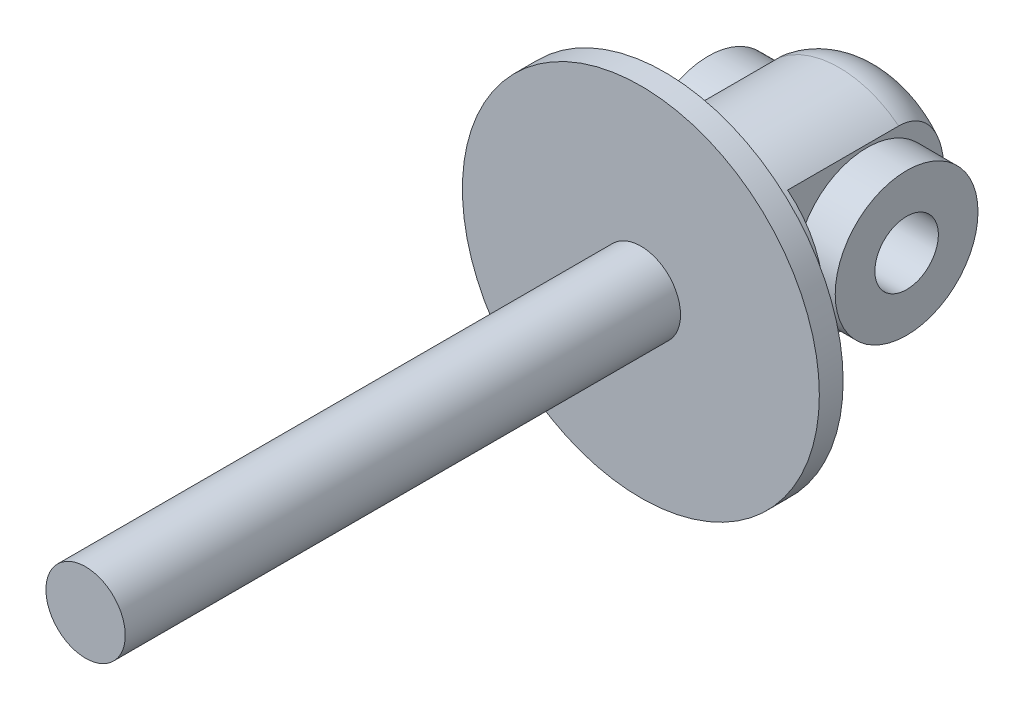
SolidWorks part; units mm, degrees
ref_plane "Front Plane" through (0, 0, 0) normal (0, 0, 1) x (1, 0, 0)
ref_plane "Top Plane" through (0, 0, 0) normal (0, 1, 0) x (1, 0, 0)
ref_plane "Right Plane" through (0, 0, 0) normal (1, 0, 0) x (0, 0, -1)
sketch "Sketch1" plane through (0, 0, 0) normal (0, 0, 1) x (1, 0, 0)
  circle A0 centre (0, 0) radius 22.5
  dimension "D1" = 45
extrude "Boss-Extrude1" add sketch "Sketch1" along normal blind 3 contours A0
sketch "Sketch2" plane through (0, 0, 3) normal (0, 0, 1) x (1, 0, 0)
  circle A0 centre (0, 0) radius 5
  dimension "D1" = 10
extrude "Boss-Extrude2" add sketch "Sketch2" along normal blind 70
sketch "Sketch3" plane through (0, 0, 0) normal (0, 0, -1) x (-1, 0, 0)
  circle A0 centre (0, 0) radius 12
  dimension "D1" = 24
extrude "Boss-Extrude3" add sketch "Sketch3" along normal blind 28
fillet "Fillet1" radius 6 1 edges at (-12, 0, -28)
sketch "Sketch4" plane through (0, 0, 0) normal (0, 1, 0) x (1, 0, 0)
  line L0 (0, 28) -> (0, -82.8651) construction
  line L1 (6, 28) -> (-6, 28) construction
  line L2 (7.5, 28) -> (33.3922, 28)
  line L3 (33.3922, 28) -> (33.3922, 8)
  line L4 (33.3922, 8) -> (7.5, 8)
  line L5 (7.5, 8) -> (7.5, 28)
  line L6 (-7.5, 8) -> (-7.5, 28)
  line L7 (-33.3922, 8) -> (-7.5, 8)
  line L8 (-33.3922, 28) -> (-33.3922, 8)
  line L9 (-7.5, 28) -> (-33.3922, 28)
  dimension "D1" = 15
  dimension "D2" = 20
extrude "Cut-Extrude1" cut sketch "Sketch4" against normal through all both and the other way through all
sketch "Sketch5" plane through (-7.5, 0, 0) normal (-1, 0, 0) x (0, 0, 1)
  line L0 (-28, 0) -> (0, 0) construction
  line L1 (-28, 6) -> (-28, -6) construction
  circle A1 centre (-18, 0) radius 4
  dimension "D1" = 8
  dimension "D2" = 10
extrude "Cut-Extrude3" cut sketch "Sketch5" against normal through all contours A1
sketch "Sketch8" plane through (0, 0, 0) normal (1, 0, 0) x (0, 0, -1)
  circle A0 centre (18, 0) radius 9
  circle A1 centre (18, 0) radius 4 construction
  circle A2 centre (18, 0) radius 4
  dimension "D1" = 18
extrude "Boss-Extrude4" add sketch "Sketch8" along normal mid plane 25
